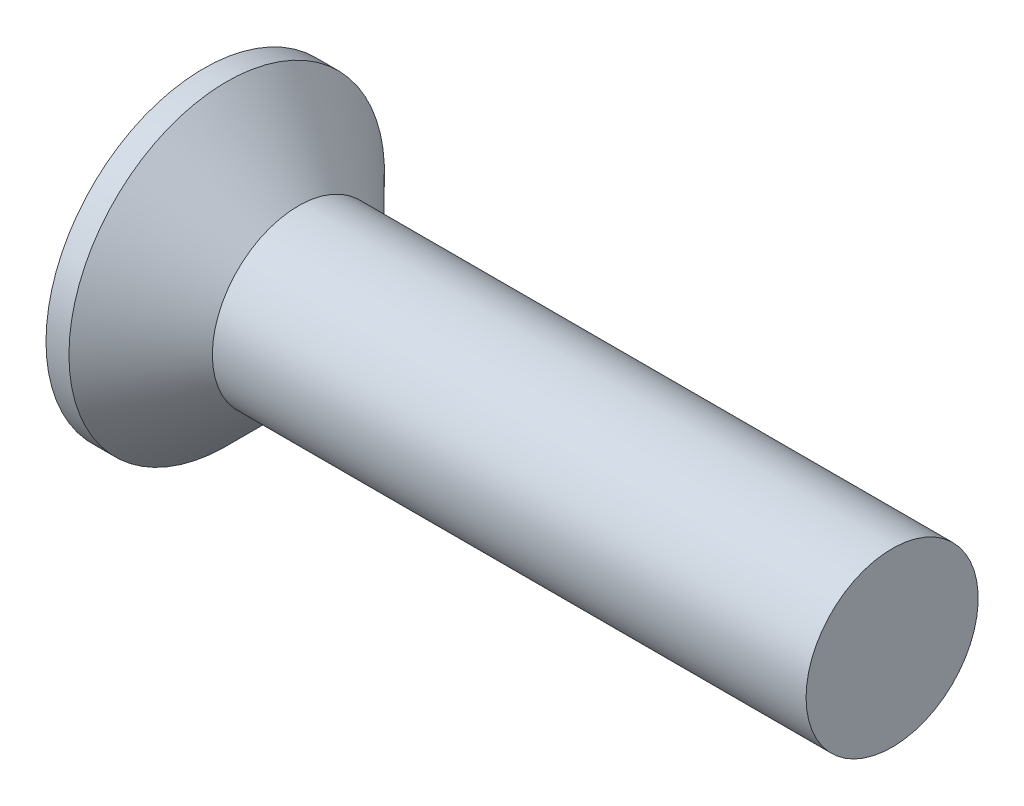
SolidWorks part; units mm, degrees
ref_plane "Plan de face" through (0, 0, 0) normal (0, 0, 1) x (1, 0, 0)
ref_plane "Plan de dessus" through (0, 0, 0) normal (0, 1, 0) x (1, 0, 0)
ref_plane "Plan de droite" through (0, 0, 0) normal (1, 0, 0) x (0, 0, -1)
sketch "Esquisse1" plane through (0, 0, 0) normal (0, 0, 1) x (1, 0, 0)
  line L0 (0, 0) -> (12, 0)
  line L1 (12, 0) -> (12, 1.5)
  line L2 (12, 1.5) -> (1.65, 1.5)
  line L4 (0, 2.75) -> (0, 0)
  line L5 (0, 2.75) -> (0.4, 2.75)
  line L6 (0.4, 2.75) -> (1.65, 1.5)
  dimension "D1" = 12
  dimension "D2" = 1.5
  dimension "D3" = 2.75
  dimension "D4" = 1.65
  dimension "D5" = 45
revolve "Révolution1" add sketch "Esquisse1" angle 360 about L0
equation "\"D3@Esquisse1\"=5.5/2"
